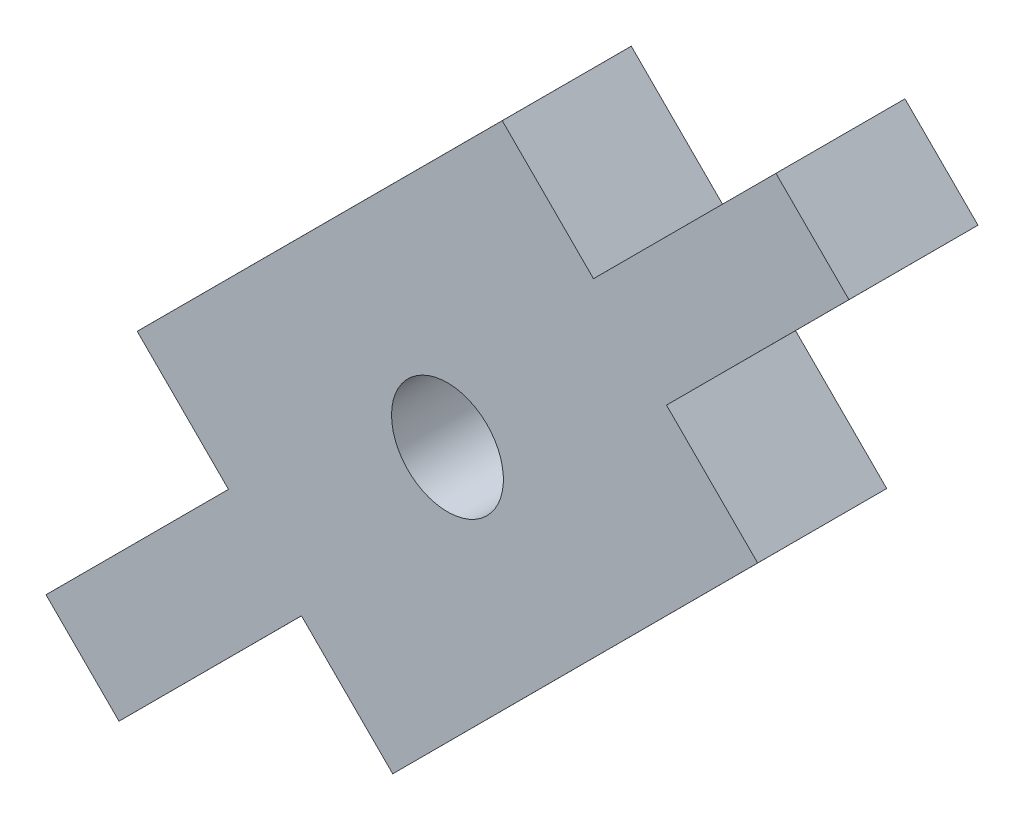
SolidWorks part; units mm, degrees
ref_plane "前视基准面" through (0, 0, 0) normal (0, 0, 1) x (1, 0, 0)
ref_plane "上视基准面" through (0, 0, 0) normal (0, 1, 0) x (1, 0, 0)
ref_plane "右视基准面" through (0, 0, 0) normal (1, 0, 0) x (0, 0, -1)
ref_plane "基准面1" through (0, 0, -0.3629) normal (0, 0, 1) x (1, 0, 0)
sketch "草图1" plane through (0, 0, -0.3629) normal (0, 0, 1) x (1, 0, 0)
  line L0 (-3.6763, 21.3222) -> (-1.5545, 19.201)
  line L1 (-1.5545, 19.201) -> (-5.7969, 14.9575)
  line L2 (-5.7969, 14.9575) -> (-4.0998, 13.2597)
  line L3 (-4.0998, 13.2597) -> (0.1425, 17.5032)
  line L4 (0.1425, 17.5032) -> (2.2643, 15.3821)
  line L5 (2.2643, 15.3821) -> (10.7491, 23.8693)
  line L6 (10.7491, 23.8693) -> (8.6291, 25.9887)
  line L7 (8.6291, 25.9887) -> (12.8714, 30.2322)
  line L8 (12.8714, 30.2322) -> (11.1732, 31.9279)
  line L9 (11.1732, 31.9279) -> (6.932, 27.6854)
  line L10 (6.932, 27.6854) -> (4.8102, 29.8066)
  line L11 (4.8102, 29.8066) -> (-3.6763, 21.3222)
  circle A0 centre (3.5366, 22.594) radius 1.3
extrude "凸台-拉伸1" add sketch "草图1" against normal blind 3
